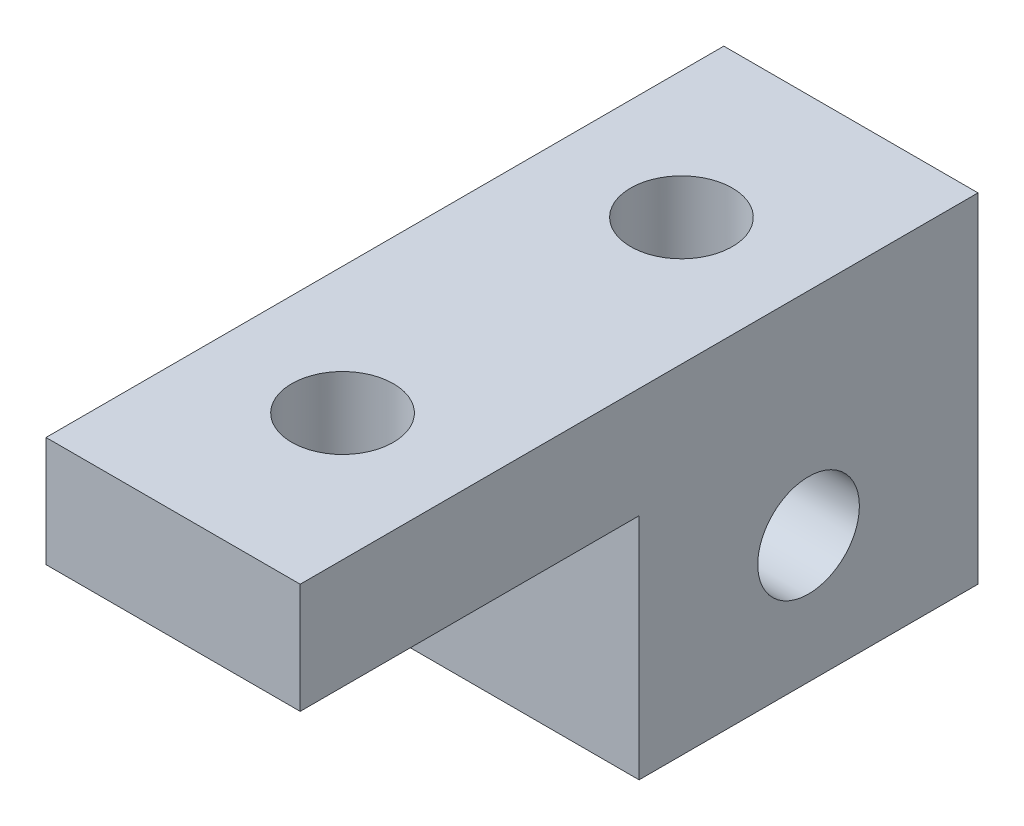
SolidWorks part; units mm, degrees
ref_plane "前视基准面" through (0, 0, 0) normal (0, 0, 1) x (1, 0, 0)
ref_plane "上视基准面" through (0, 0, 0) normal (0, 1, 0) x (1, 0, 0)
ref_plane "右视基准面" through (0, 0, 0) normal (1, 0, 0) x (0, 0, -1)
other "Configuration Table"
sketch "草图1" plane through (0, 0, 0) normal (1, 0, 0) x (0, 0, -1)
  line L1 (-2, 1) -> (2, 1)
  line L2 (-2, 1) -> (-2, -1.5)
  line L3 (-2, -1.5) -> (2, -1.5)
  line L4 (2, 1) -> (2, -1.5)
  line L5 (-2, 1) -> (2, 1)
  line L6 (-2, 1) -> (-2, 2.5)
  line L7 (-2, 2.5) -> (2, 2.5)
  line L8 (2, 1) -> (2, 2.5)
  line L9 (-2, 2.5) -> (-6, 2.5)
  line L10 (-2, 2.5) -> (-2, 1)
  line L11 (-2, 1) -> (-6, 1)
  line L12 (-6, 2.5) -> (-6, 1)
  circle A0 centre (0, 0) radius 0.6
  point P6 (0, -1.5)
  dimension "D1" = 1.2
  dimension "D2" = 1.5
  dimension "D3" = 2
  dimension "D4" = 1.5
  dimension "D5" = 4
  dimension "D6" = 1
extrude "凸台-拉伸1" add sketch "草图1" along normal blind 3 contours L4 L1 L2 L3 A0 | L1 L8 L7 L6 | L9 L12 L11 L6
sketch "草图3" plane through (0, 1, 0) normal (0, -1, 0) x (1, 0, 0)
  line L0 (3, 6) -> (0, 6) construction
  line L1 (3, -2) -> (0, -2) construction
  circle A0 centre (1.5, 4) radius 0.6
  circle A1 centre (1.5, 0) radius 0.6
  point P5 (1.5, 6)
  dimension "D2" = 1.2
  dimension "D1" = 2
  dimension "D3" = 2
extrude "切除-拉伸1" cut sketch "草图3" against normal through all both and the other way through all contours A0 | A1
sketch "草图5" plane through (3, 0, 0) normal (1, 0, 0) x (0, 0, -1)
  line L0 (-6, 2.5) -> (-6, 1) construction
  line L1 (-2, 1.2) -> (-6, 1.2)
  line L2 (-2, 1.2) -> (-2, 1)
  line L3 (-2, 1) -> (-6, 1)
  line L4 (-6, 1.2) -> (-6, 1)
  line L5 (-2, 1) -> (-6, 1) construction
  line L6 (-2, 1) -> (-2, -1.5) construction
  dimension "D1" = 0.2
extrude "切除-拉伸2" cut sketch "草图5" against normal through all contours L1 L4 L3 L2
